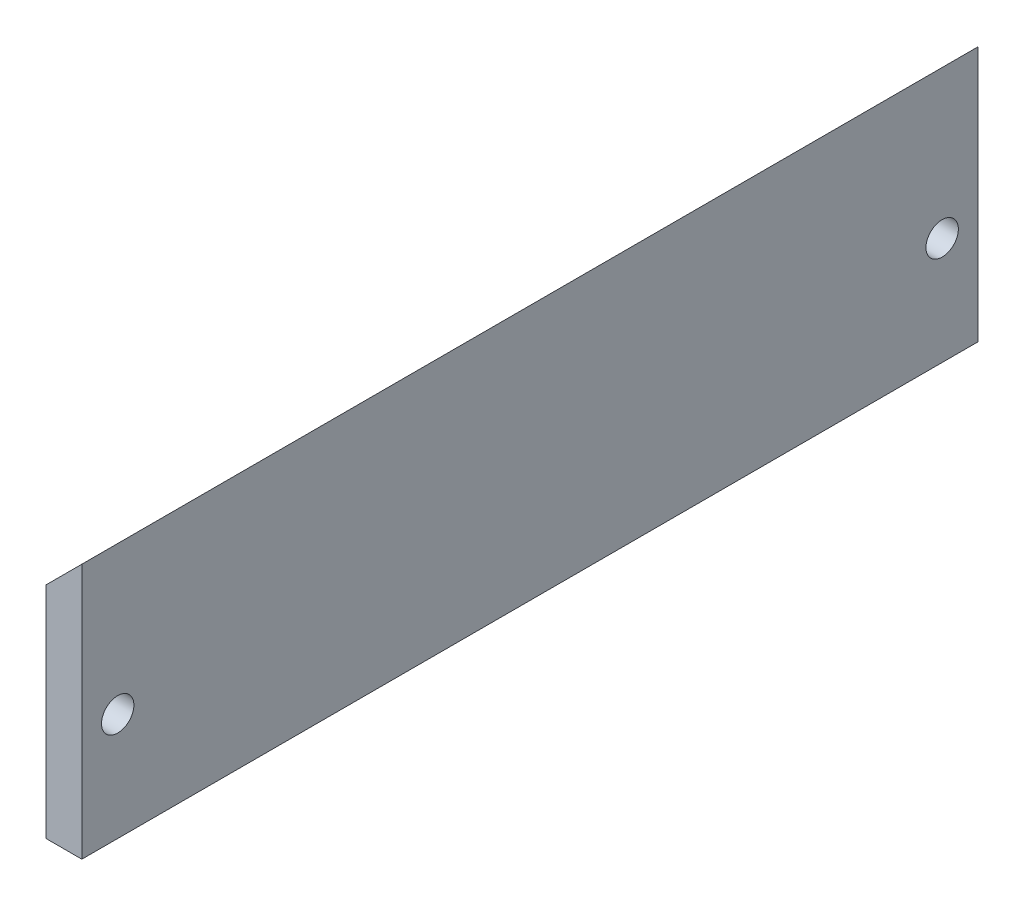
SolidWorks part; units mm, degrees
material "6061-T6 (SS)"
ref_plane "Front" through (0, 0, 0) normal (0, 0, 1) x (1, 0, 0)
ref_plane "Top" through (0, 0, 0) normal (0, 1, 0) x (1, 0, 0)
ref_plane "Right" through (0, 0, 0) normal (1, 0, 0) x (0, 0, -1)
sketch "Sketch1" plane through (0, 0, 0) normal (1, 0, 0) x (0, 0, -1)
  line L0 (0, 0) -> (0, -32.2534) construction
  line L1 (0, 0) -> (39.6875, 0)
  line L2 (0, 0) -> (0, 22.6314)
  line L3 (0, 22.6314) -> (39.6875, 22.6314)
  line L4 (39.6875, 0) -> (39.6875, 22.6314)
  circle A0 centre (36.5125, 9.525) radius 1.4351
  dimension "D4" = 3.175
  dimension "D5" = 2.8702
  dimension "D1" = 79.375
  dimension "D2" = 22.6314
  dimension "D3" = 9.525
extrude "Boss-Extrude1" add sketch "Sketch1" against normal blind 6.35
sketch "Sketch2" plane through (0, 0, 0) normal (0, -1, 0) x (1, 0, 0)
  line L0 (0, 0) -> (0, -39.6875) construction
  line L1 (-6.35, -39.6875) -> (-3.175, -39.6875)
  line L2 (-6.35, -39.6875) -> (-6.35, -33.3375)
  line L3 (-6.35, -33.3375) -> (-3.175, -33.3375)
  line L4 (-3.175, -39.6875) -> (-3.175, -33.3375)
  dimension "D1" = 3.175
  dimension "D2" = 6.35
extrude "Cut-Extrude1" cut sketch "Sketch2" against normal through all
sketch "Sketch3" plane through (0, 0, 0) normal (0, 0, 1) x (1, 0, 0)
  line L0 (0, 22.6314) -> (-6.35, 16.2814)
  line L1 (-6.35, 22.6314) -> (-6.35, 0) construction
  line L2 (-6.35, 16.2814) -> (-6.35, 22.6314)
  line L3 (-6.35, 22.6314) -> (0, 22.6314) construction
  line L4 (-6.35, 22.6314) -> (0, 22.6314)
  dimension "D1" = 45
extrude "Cut-Extrude2" cut sketch "Sketch3" against normal through all
hole_wizard "#4-40 Tapped Hole1" positions "Sketch5" profile "Sketch4" tap size "#4-40" standard "Ansi Inch"
sketch "Sketch5" plane through (0, 0, 0) normal (0, -1, 0) x (1, 0, 0)
  line L0 (-3.175, -39.6875) -> (0, -39.6875) construction
  line L4 (-3.175, -33.3375) -> (-3.175, -20.6375) construction
  point P0 (-3.175, -20.6375)
  dimension "D1" = 19.05
sketch "Sketch4" plane through (-3.175, 0, -20.6375) normal (1, 0, 0) x (0, 0, -1)
  line L0 (0, 0) -> (0, 10.3312)
  line L1 (0, 10.3312) -> (1.1303, 9.652)
  line L2 (1.1303, 9.652) -> (1.1303, 0)
  line L5 (1.1303, 0) -> (0, 0)
  line L10 (0, 10.3312) -> (-1.1303, 9.652) construction
  line L11 (0, -6.35) -> (0, 107.95) construction
  dimension "Tap Drill Dia." = 2.2606
  dimension "Tap Drill Depth" = 9.652
  dimension "Drill Angle" = 118
cosmetic thread "Hole Thread1" parameters "D1"=6.35, "D2"=2.8448
mirror "Mirror1" about plane through (-6.35, 0, 0) normal (0, 0, 1) of bodies 104
